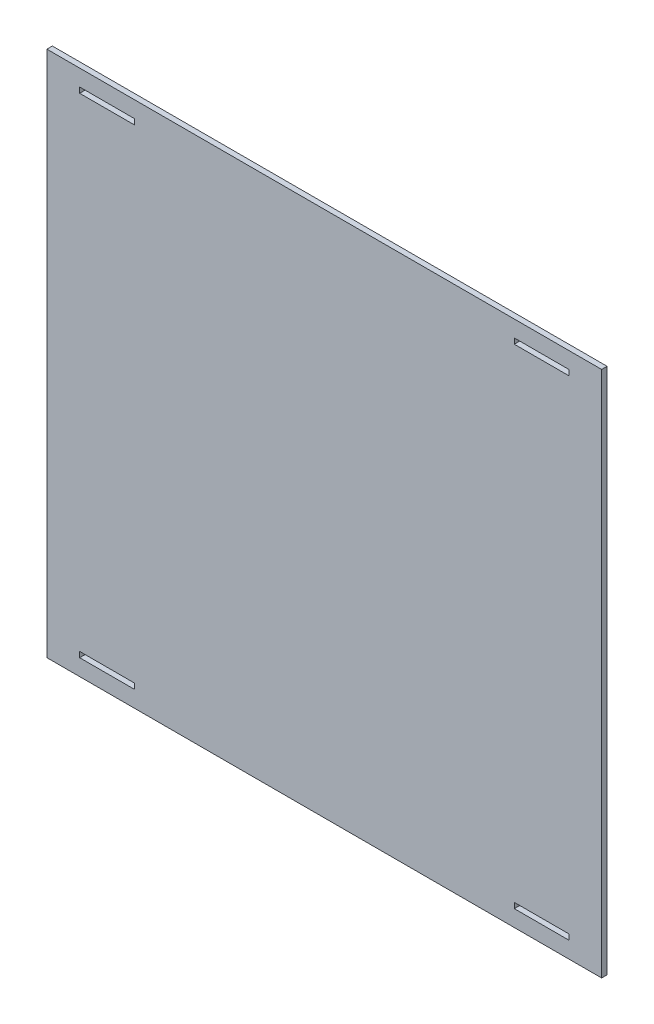
SolidWorks part; units mm, degrees
material "CA"
ref_plane "Front Plane" through (0, 0, 0) normal (0, 0, 1) x (1, 0, 0)
ref_plane "Top Plane" through (0, 0, 0) normal (0, 1, 0) x (1, 0, 0)
ref_plane "Right Plane" through (0, 0, 0) normal (1, 0, 0) x (0, 0, -1)
sketch "Sketch1" plane through (0, 0, 0) normal (0, 0, 1) x (1, 0, 0)
  line L1 (0, 0) -> (-508, 0)
  line L2 (0, 0) -> (0, 482.6)
  line L3 (0, 482.6) -> (-508, 482.6)
  line L4 (-508, 0) -> (-508, 482.6)
  dimension "D1" = 508
  dimension "D2" = 482.6
extrude "Boss-Extrude1" add sketch "Sketch1" along normal blind 5
sketch "Sketch2" plane through (0, 0, 5) normal (0, 0, 1) x (1, 0, 0)
  line L5 (-478, 467.6) -> (-428, 467.6)
  line L6 (-478, 467.6) -> (-478, 462.6)
  line L7 (-478, 462.6) -> (-428, 462.6)
  line L8 (-428, 467.6) -> (-428, 462.6)
  line L13 (-30, 467.6) -> (-80, 467.6)
  line L14 (-30, 467.6) -> (-30, 462.6)
  line L15 (-30, 462.6) -> (-80, 462.6)
  line L16 (-80, 467.6) -> (-80, 462.6)
  line L21 (-30, 15) -> (-80, 15)
  line L22 (-30, 15) -> (-30, 20)
  line L23 (-30, 20) -> (-80, 20)
  line L24 (-80, 15) -> (-80, 20)
  line L29 (-478, 20) -> (-428, 20)
  line L30 (-478, 20) -> (-478, 15)
  line L31 (-478, 15) -> (-428, 15)
  line L32 (-428, 20) -> (-428, 15)
  line L33 (-508, 0) -> (0, 0) construction
  line L34 (-508, 482.6) -> (-508, 0) construction
  line L35 (0, 482.6) -> (-508, 482.6) construction
  line L37 (0, 0) -> (0, 482.6) construction
  dimension "D3" = 50
  dimension "D4" = 5
  dimension "D5" = 50
  dimension "D6" = 5
  dimension "D7" = 15
  dimension "D8" = 30
  dimension "D9" = 30
  dimension "D10" = 15
  dimension "D11" = 50
  dimension "D12" = 5
  dimension "D13" = 30
  dimension "D14" = 5
  dimension "D15" = 50
  dimension "D17" = 15
  dimension "D21" = 30
  dimension "D24" = 15
extrude "Cut-Extrude1" cut sketch "Sketch2" against normal blind 5
